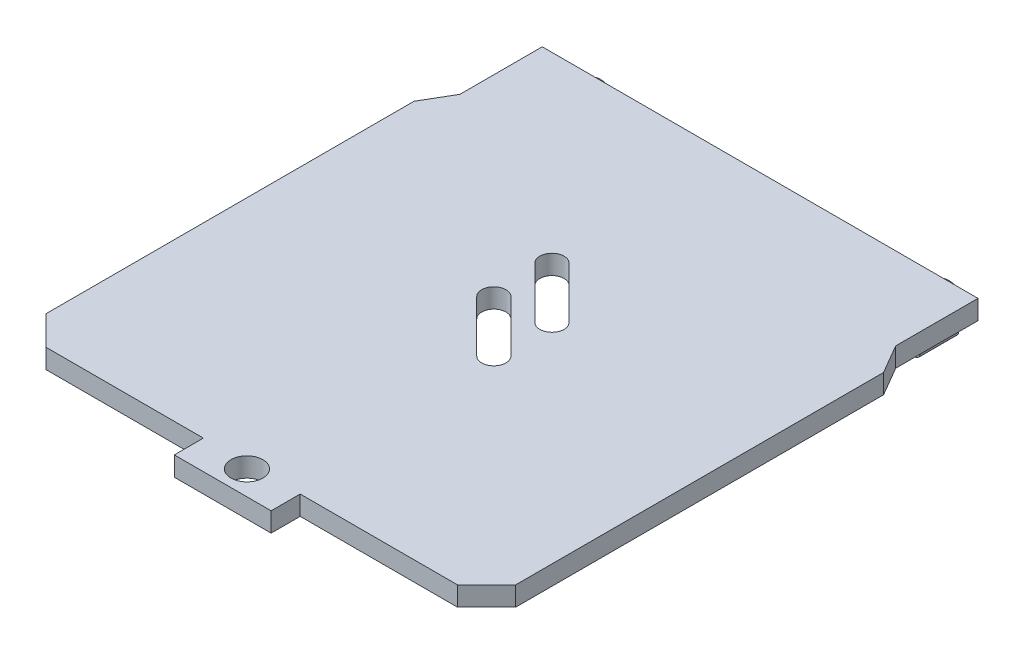
SolidWorks part; units mm, degrees
material "镁合金_CNC_暂定1800kg_m3"
ref_plane "前视基准面" through (0, 0, 0) normal (0, 0, 1) x (1, 0, 0)
ref_plane "上视基准面" through (0, 0, 0) normal (0, 1, 0) x (1, 0, 0)
ref_plane "右视基准面" through (0, 0, 0) normal (1, 0, 0) x (0, 0, -1)
other "Configuration Table"
sketch "草图1" plane through (0, 0, 0) normal (0, 1, 0) x (1, 0, 0)
  line L0 (-22.5, -3.5) -> (-22.5, -12)
  line L1 (-22.5, -12) -> (-24.25, -15)
  line L2 (-24.25, -15) -> (-24.25, -53)
  line L3 (-24.25, -53) -> (-21.25, -56)
  line L4 (-21.25, -56) -> (-5, -56)
  line L5 (-5, -56) -> (-5, -59)
  line L6 (-5, -59) -> (5, -59)
  line L7 (5, -59) -> (5, -56)
  line L8 (5, -56) -> (21.25, -56)
  line L9 (21.25, -56) -> (24.25, -53)
  line L10 (24.25, -53) -> (24.25, -15)
  line L11 (24.25, -15) -> (22.5, -12)
  line L12 (22.5, -12) -> (22.5, -3.5)
  line L13 (22.5, -3.5) -> (-22.5, -3.5)
  circle A0 centre (0, -56.5) radius 1.65
extrude "两毫米后换电盖_下缘保留扎带通道" add sketch "草图1" along normal blind 2 from offset 90
sketch "草图2" plane through (0, 0, 0) normal (0, 0, 1) x (1, 0, 0)
  line L0 (-20.5, 88) -> (-15.5, 88)
  line L1 (-15, 88.5) -> (-15, 89.5)
  line L2 (-15.5, 90) -> (-20.5, 90)
  line L3 (-21, 89.5) -> (-21, 88.5)
  arc A0 (-15.5, 88) -> (-15, 88.5) centre (-15.5, 88.5) ccw
  arc A1 (-15, 89.5) -> (-15.5, 90) centre (-15.5, 89.5) ccw
  arc A2 (-20.5, 90) -> (-21, 89.5) centre (-20.5, 89.5) ccw
  arc A3 (-21, 88.5) -> (-20.5, 88) centre (-20.5, 88.5) ccw
extrude "内侧下定位舌_-1" add sketch "草图2" along normal blind 4 from offset 4
sketch "草图3" plane through (0, 0, 0) normal (0, 0, 1) x (1, 0, 0)
  circle A0 centre (-18, 89) radius 1.6
extrude "下插定位销_D3p2_-1" add sketch "草图3" along normal blind 2 from offset 2
sketch "草图4" plane through (0, 0, 0) normal (0, 0, 1) x (1, 0, 0)
  line L0 (15.5, 88) -> (20.5, 88)
  line L1 (21, 88.5) -> (21, 89.5)
  line L2 (20.5, 90) -> (15.5, 90)
  line L3 (15, 89.5) -> (15, 88.5)
  arc A0 (20.5, 88) -> (21, 88.5) centre (20.5, 88.5) ccw
  arc A1 (21, 89.5) -> (20.5, 90) centre (20.5, 89.5) ccw
  arc A2 (15.5, 90) -> (15, 89.5) centre (15.5, 89.5) ccw
  arc A3 (15, 88.5) -> (15.5, 88) centre (15.5, 88.5) ccw
extrude "内侧下定位舌_1" add sketch "草图4" along normal blind 4 from offset 4
sketch "草图5" plane through (0, 0, 0) normal (0, 0, 1) x (1, 0, 0)
  circle A0 centre (18, 89) radius 1.6
extrude "下插定位销_D3p2_1" add sketch "草图5" along normal blind 2 from offset 2
sketch "草图6" plane through (0, 0, 0) normal (0, 1, 0) x (1, 0, 0)
  line L0 (-1.7678, -21.4645) -> (3.5355, -26.7678)
  line L1 (1.7678, -28.5355) -> (-3.5355, -23.2322)
  line L2 (-1.7678, -27.4645) -> (3.5355, -32.7678)
  line L3 (1.7678, -34.5355) -> (-3.5355, -29.2322)
  arc A0 (3.5355, -26.7678) -> (1.7678, -28.5355) centre (2.6517, -27.6517) cw
  arc A1 (-3.5355, -23.2322) -> (-1.7678, -21.4645) centre (-2.6517, -22.3483) cw
  arc A2 (3.5355, -32.7678) -> (1.7678, -34.5355) centre (2.6517, -33.6517) cw
  arc A3 (-3.5355, -29.2322) -> (-1.7678, -27.4645) centre (-2.6517, -28.3483) cw
extrude "后盖45度平行通气孔" cut sketch "草图6" along normal blind 2 from offset 90
